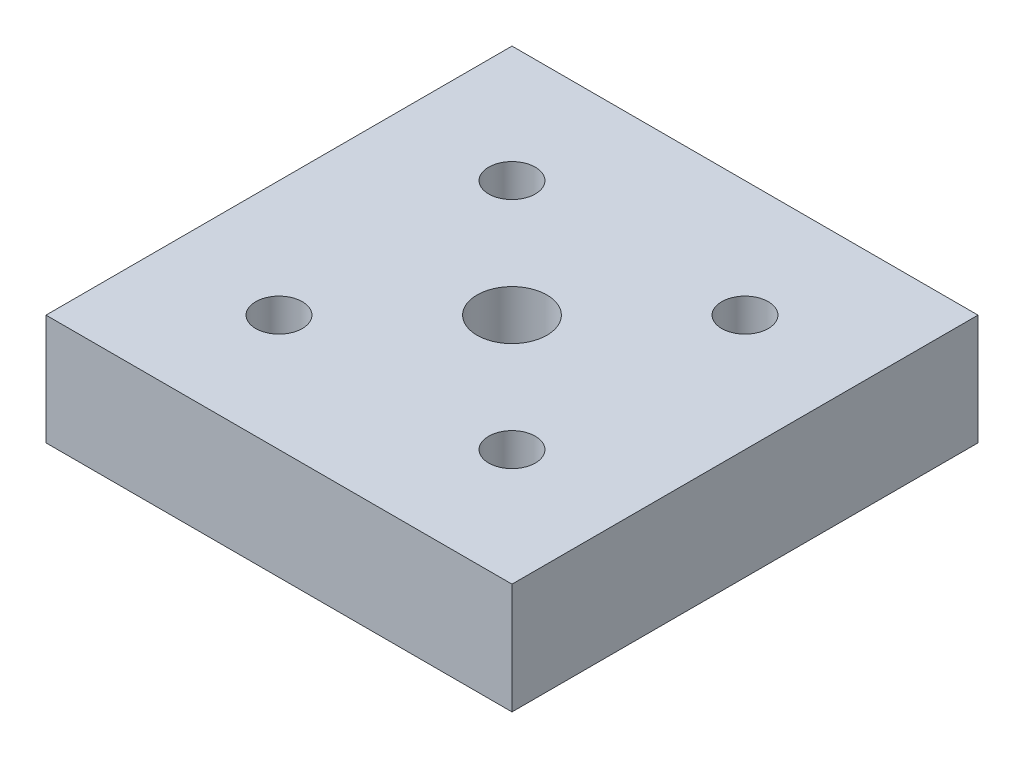
SolidWorks part; units mm, degrees
ref_plane "Front Plane" through (0, 0, 0) normal (0, 0, 1) x (1, 0, 0)
ref_plane "Top Plane" through (0, 0, 0) normal (0, 1, 0) x (1, 0, 0)
ref_plane "Right Plane" through (0, 0, 0) normal (1, 0, 0) x (0, 0, -1)
sketch "Sketch1" plane through (0, 0, 0) normal (0, 1, 0) x (1, 0, 0)
  line L1 (-20, 20) -> (20, 20) construction
  line L2 (-20, 20) -> (-20, -20) construction
  line L3 (-20, -20) -> (20, -20) construction
  line L4 (20, 20) -> (20, -20) construction
  line L5 (-20, 20) -> (20, -20) construction
  line L6 (-20, -20) -> (20, 20) construction
  line L7 (-40, 40) -> (40, 40)
  line L8 (-40, 40) -> (-40, -40)
  line L9 (-40, -40) -> (40, -40)
  line L10 (40, 40) -> (40, -40)
  line L11 (-40, 40) -> (40, -40) construction
  line L12 (-40, -40) -> (40, 40) construction
  circle A0 centre (-20, 20) radius 4
  circle A1 centre (20, 20) radius 4
  circle A2 centre (20, -20) radius 4
  circle A3 centre (-20, -20) radius 4
  circle A4 centre (0, 0) radius 6
  point P0 (0, 0)
  dimension "D3" = 12
  dimension "D4" = 8
  dimension "D1" = 40
  dimension "D2" = 80
extrude "Boss-Extrude1" add sketch "Sketch1" along normal blind 19
sketch "Sketch2" plane through (0, 0, 0) normal (0, 1, 0) x (1, 0, 0)
  line L1 (-20, -20) -> (20, -20) construction
  line L2 (-20, -20) -> (-20, 20) construction
  line L3 (-20, 20) -> (20, 20) construction
  line L4 (20, -20) -> (20, 20) construction
  line L5 (-20, -20) -> (20, 20) construction
  line L6 (-20, 20) -> (20, -20) construction
  circle A0 centre (-20, 20) radius 7
  circle A1 centre (20, 20) radius 7
  circle A2 centre (20, -20) radius 7
  circle A3 centre (-20, -20) radius 7
  point P0 (0, 0)
  dimension "D2" = 14
  dimension "D1" = 40
extrude "Cut-Extrude1" cut sketch "Sketch2" along normal blind 8
